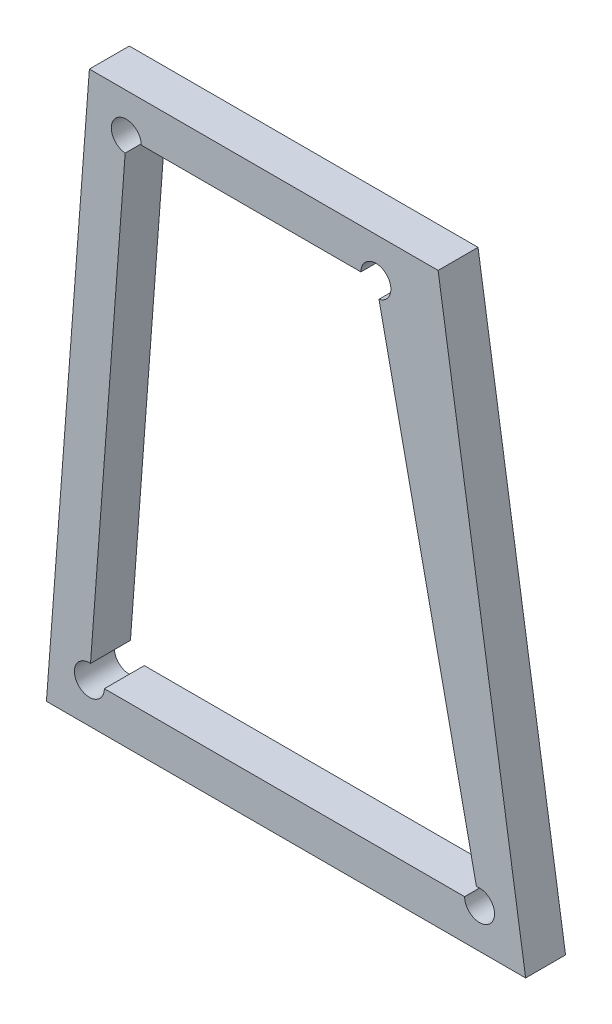
SolidWorks part; units mm, degrees
ref_plane "Спереди" through (0, 0, 0) normal (0, 0, 1) x (1, 0, 0)
ref_plane "Сверху" through (0, 0, 0) normal (0, 1, 0) x (1, 0, 0)
ref_plane "Справа" through (0, 0, 0) normal (1, 0, 0) x (0, 0, -1)
sketch "Эскиз1" plane through (0, 0, 0) normal (0, 0, 1) x (1, 0, 0)
  line L1 (0, 0) -> (48, 0)
  line L3 (4.3019, 57) -> (39.2319, 57)
  line L4 (4.3019, 57) -> (0, 0)
  line L5 (39.2319, 57) -> (48, 0)
  line L6 (4.4148, 5.4957) -> (7.8871, 51.5043)
  line L8 (9.5, 53) -> (31.5, 53)
  line L10 (43.0737, 5.4674) -> (33.311, 51.5326)
  line L11 (41.8847, 4) -> (5.8019, 4)
  arc A0 (33.311, 51.5326) -> (31.5, 53) centre (33, 53) ccw
  arc A1 (9.5, 53) -> (7.8871, 51.5043) centre (8, 53) ccw
  arc A2 (4.4148, 5.4957) -> (5.8019, 4) centre (4.3019, 4) ccw
  arc A3 (41.8847, 4) -> (43.0737, 5.4674) centre (43.3847, 4) ccw
  point P10 (44.5501, 3.0557)
  dimension "D1" = 57
  dimension "D2" = 34.93
  dimension "D3" = 46.0652
  dimension "D4" = 48
  dimension "D5" = 36.0828
  dimension "D6" = 46.0085
  dimension "D7" = 22
  dimension "D8" = 1.5
extrude "Бобышка-Вытянуть1" add sketch "Эскиз1" along normal blind 4
